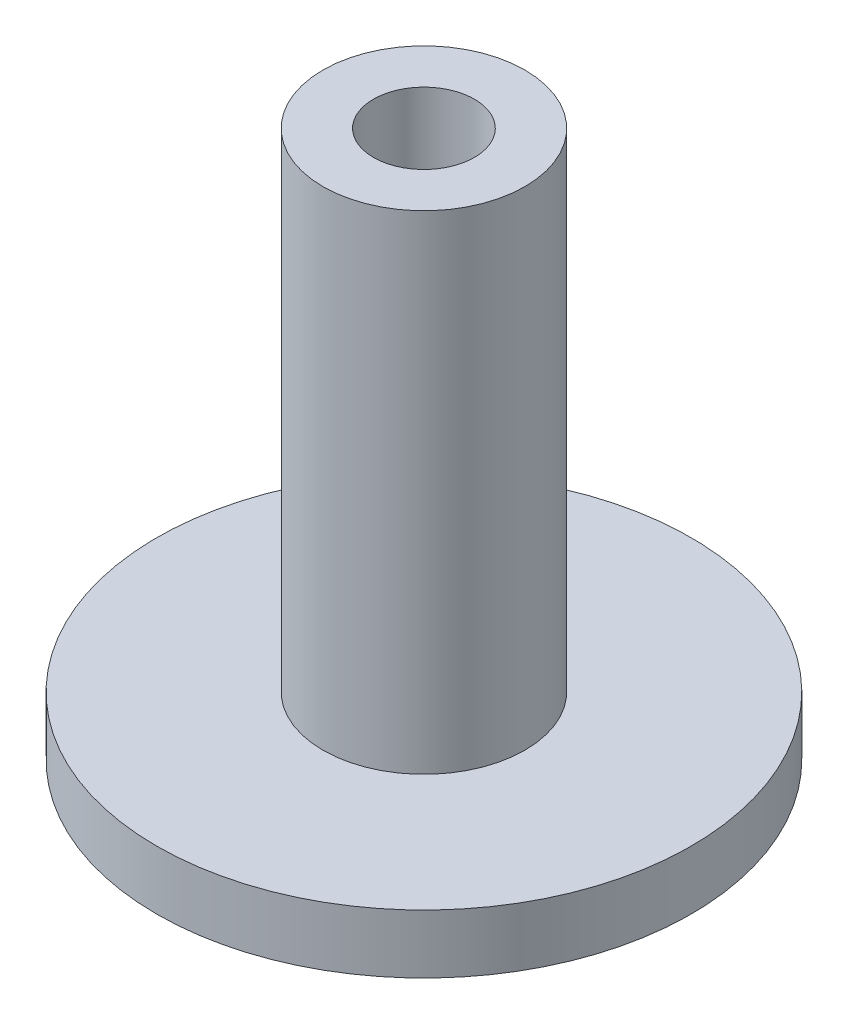
SolidWorks part; units mm, degrees
ref_plane "Front Plane" through (0, 0, 0) normal (0, 0, 1) x (1, 0, 0)
ref_plane "Top Plane" through (0, 0, 0) normal (0, 1, 0) x (1, 0, 0)
ref_plane "Right Plane" through (0, 0, 0) normal (1, 0, 0) x (0, 0, -1)
sketch "Sketch1" plane through (0, 0, 0) normal (0, 1, 0) x (1, 0, 0)
  circle A0 centre (0, 0) radius 6.35
  dimension "D1" = 12.7
extrude "Boss-Extrude1" add sketch "Sketch1" along normal blind 1.4
sketch "Sketch2" plane through (0, 1.4, 0) normal (0, 1, 0) x (1, 0, 0)
  circle A0 centre (0, 0) radius 2.4
  dimension "D1" = 4.8
extrude "Boss-Extrude2" add sketch "Sketch2" along normal blind 11.6
sketch "Sketch3" plane through (0, 13, 0) normal (0, 1, 0) x (1, 0, 0)
  circle A0 centre (0, 0) radius 1.2
  circle A1 centre (0, 0) radius 2.4 construction
  dimension "D1" = 1.2
extrude "Cut-Extrude1" cut sketch "Sketch3" against normal through all
